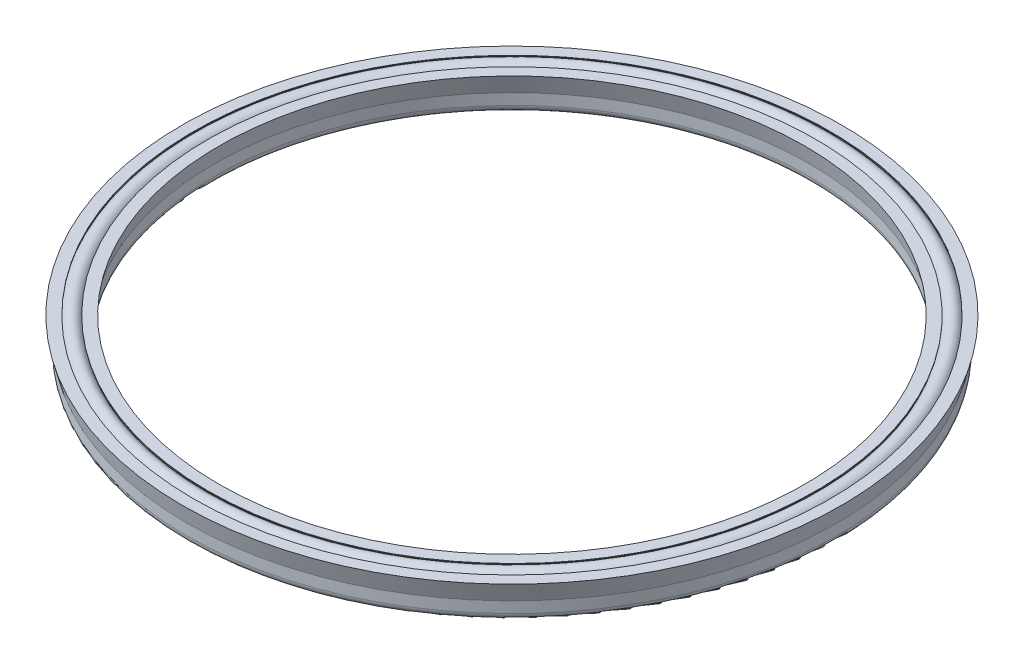
SolidWorks part; units mm, degrees
material "Neoprene Rubber-60A Durometer"
ref_plane "Front Plane" through (0, 0, 0) normal (0, 0, 1) x (1, 0, 0)
ref_plane "Top Plane" through (0, 0, 0) normal (0, 1, 0) x (1, 0, 0)
ref_plane "Right Plane" through (0, 0, 0) normal (1, 0, 0) x (0, 0, -1)
sketch "Sketch1" plane through (0, 0, 0) normal (0, 0, 1) x (1, 0, 0)
  line L0 (0, 0) -> (0, -9.4095) construction
  line L1 (0, 0) -> (-50.8, 0) construction
  line L5 (-55.0862, -6.2484) -> (-52.8637, -6.2484)
  line L6 (-57.15, 0) -> (-55.1961, 0)
  line L7 (-56.3562, -3.0734) -> (-56.3562, -4.9784)
  line L8 (-51.5937, -3.0734) -> (-51.5937, -4.9784)
  line L9 (-56.3562, -3.0734) -> (-57.15, 0)
  line L10 (-51.5937, -3.0734) -> (-50.8, 0)
  line L11 (-55.1961, -0.1217) -> (-55.1961, 0)
  line L12 (-52.7538, -0.1217) -> (-52.7538, 0)
  line L13 (-52.7538, 0) -> (-50.8, 0)
  arc A0 (-55.1961, -0.1217) -> (-52.7538, -0.1217) centre (-53.975, -1.1361) ccw
  arc A1 (-56.3562, -4.9784) -> (-55.0862, -6.2484) centre (-55.0862, -4.9784) ccw
  arc A2 (-52.8637, -6.2484) -> (-51.5937, -4.9784) centre (-52.8637, -4.9784) ccw
  circle A3 centre (-53.975, -1.1361) radius 1.4684
  dimension "D1" = 101.6
  dimension "D2" = 6.35
revolve "Revolve1" add sketch "Sketch1" angle 360 about L0
